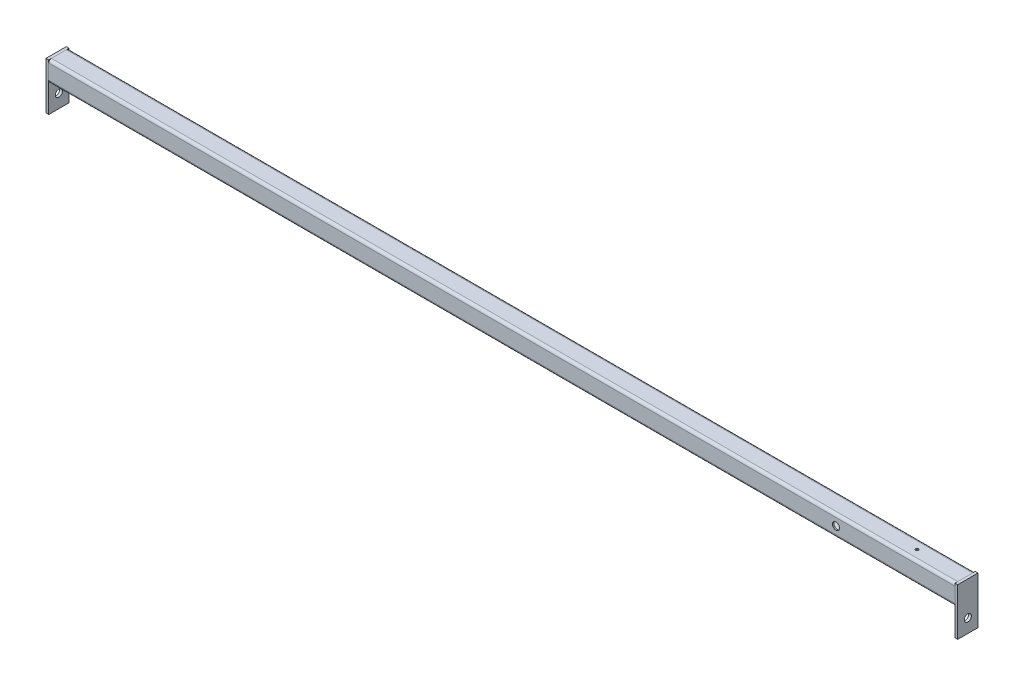
SolidWorks part; units mm, degrees
other "DetailItem1"
other "DetailItem2"
other "Weld Folder"
other "Weld Bead1"
other "Weld Bead2"
material "AISI 304"
ref_plane "Front Plane" through (0, 0, 0) normal (0, 0, 1) x (1, 0, 0)
ref_plane "Top Plane" through (0, 0, 0) normal (0, 1, 0) x (1, 0, 0)
ref_plane "Right Plane" through (0, 0, 0) normal (1, 0, 0) x (0, 0, -1)
sketch3d "3DStructure"
  line L0 (0, 0, 0) -> (0, 70, 0)
  line L2 (1344, 70, 0) -> (1344, 0, 0)
  line L3 (0, 55, 0) -> (1344, 55, 0)
  dimension "D3" = 15
  dimension "D1" = 1344
  dimension "D2" = 15
  dimension "D4" = 70
other "Square tube - configured 30 X 30 X 2"
ref_plane "Plane1" through (0, 55, 0) normal (1, 0, 0) x (0, 0, -1)
sketch "Sketch1" plane through (0, 55, 0) normal (1, 0, 0) x (0, 0, -1)
  line L0 (-11, -13) -> (11, -13)
  line L1 (-13, -11) -> (-13, 11)
  line L2 (11, 13) -> (-11, 13)
  line L3 (13, 11) -> (13, -11)
  line L4 (-11, -15) -> (11, -15)
  line L5 (-15, -11) -> (-15, 11)
  line L6 (11, 15) -> (-11, 15)
  line L7 (15, 11) -> (15, -11)
  arc A0 (15, 11) -> (11, 15) centre (11, 11) ccw
  arc A1 (11, -15) -> (15, -11) centre (11, -11) ccw
  arc A2 (-15, -11) -> (-11, -15) centre (-11, -11) ccw
  arc A3 (-11, 15) -> (-15, 11) centre (-11, 11) ccw
  arc A4 (-11, 13) -> (-13, 11) centre (-11, 11) ccw
  arc A5 (13, 11) -> (11, 13) centre (11, 11) ccw
  arc A6 (11, -13) -> (13, -11) centre (11, -11) ccw
  arc A7 (-13, -11) -> (-11, -13) centre (-11, -11) ccw
  point P0 (-15, 0)
  point P1 (15, 0)
  point P2 (0, 15)
  point P3 (0, -15)
  point P4 (0, 0)
  point P5 (-15, -15)
  point P6 (15, -15)
  point P7 (15, 15)
  point P8 (-15, 15)
  point P33 (0, 0)
  dimension "D1" = 4
  dimension "Thickness" = 2
  dimension "V_leg" = 30
other "Steel bar - configured 30 X 2"
ref_plane "Plane2" through (0, 0, 0) normal (0, 1, 0) x (1, 0, 0)
sketch "Sketch11" plane through (0, 0, 0) normal (0, 1, 0) x (1, 0, 0)
  line L9 (2, -15) -> (-2, -15)
  line L10 (2, -15) -> (2, 15)
  line L11 (2, 15) -> (-2, 15)
  line L12 (-2, -15) -> (-2, 15)
  line L13 (2, -15) -> (-2, 15) construction
  line L14 (2, 15) -> (-2, -15) construction
  point P4 (0, 0)
  point P33 (0, 0)
  point P35 (0, 0)
  dimension "D2" = 4
  dimension "D3" = 30
other "Trim/Extend1"
hole_wizard "Ø10.5 (10.5) Frame Mount Holes" positions "Sketch12" profile "Sketch13" hole size "Ø10.5" standard "ANSI Metric" end condition through all
sketch "Sketch12" plane through (1346, 0, 0) normal (1, 0, 0) x (0, 0, -1)
  line L0 (-15, 0) -> (15, 0) construction
  point P0 (0, 20)
  dimension "D1" = 20
sketch "Sketch13" plane through (1346, 20, 0) normal (0, 1, 0) x (0, 0, -1)
  line L0 (0, 0) -> (0, 1348)
  line L1 (0, 1348) -> (5.25, 1348)
  line L2 (5.25, 1348) -> (5.25, 0)
  line L5 (5.25, 0) -> (0, 0)
  line L11 (0, -6.35) -> (0, 107.95) construction
  dimension "Thru Hole Dia." = 10.5
  dimension "Thru Hole Depth" = 1348
hole_wizard "Ø10.5 (10.5) PC Shelf Mount Hole" positions "Sketch14" profile "Sketch16" hole size "Ø10.5" standard "ANSI Metric" end condition through all
sketch "Sketch14" plane through (0, 0, 15) normal (0, 0, 1) x (1, 0, 0)
  line L0 (1346, 0) -> (1346, 70) construction
  line L2 (1342, 44) -> (1342, 66) construction
  point P0 (1166, 55)
  point P11 (1342, 55)
  dimension "D1" = 180
sketch "Sketch16" plane through (1166, 55, 15) normal (1, 0, 0) x (0, -1, 0)
  line L0 (0, 0) -> (0, 30)
  line L1 (0, 30) -> (5.25, 30)
  line L2 (5.25, 30) -> (5.25, 0)
  line L5 (5.25, 0) -> (0, 0)
  line L11 (0, -6.35) -> (0, 107.95) construction
  dimension "Thru Hole Dia." = 10.5
  dimension "Thru Hole Depth" = 30
hole_wizard "Ø5.2 (5.2) Wall Mount Hole" [suppressed] positions "Sketch17" profile "Sketch18" hole size "Ø5.2" standard "ANSI Metric"
sketch "Sketch17" plane through (0, 0, 15) normal (0, 0, 1) x (1, 0, 0)
  line L1 (2, 66) -> (2, 44) construction
  line L2 (-2, 70) -> (-2, 0) construction
  point P0 (672, 55)
  point P10 (2, 55)
  dimension "D1" = 674
sketch "Sketch18" plane through (672, 55, 15) normal (1, 0, 0) x (0, -1, 0)
  line L0 (0, 0) -> (0, 35)
  line L1 (0, 35) -> (2.6, 35)
  line L2 (2.6, 35) -> (2.6, 0)
  line L5 (2.6, 0) -> (0, 0)
  line L11 (0, -6.35) -> (0, 107.95) construction
  dimension "Thru Hole Dia." = 5.2
  dimension "Thru Hole Depth" = 35
hole_wizard "Ø4.2 (4.2) PC Shelf Table Mount Hole" positions "Sketch19" profile "Sketch20" hole size "Ø4.2" standard "ANSI Metric" end condition through all
sketch "Sketch19" plane through (0, 40, 0) normal (0, -1, 0) x (-1, 0, 0)
  line L0 (-1346, -15) -> (-1346, 15) construction
  point P0 (-1271, 0)
  dimension "D1" = 75
sketch "Sketch20" plane through (1271, 40, 0) normal (1, 0, 0) x (0, 0, -1)
  line L0 (0, 0) -> (0, 30)
  line L1 (0, 30) -> (2.1, 30)
  line L2 (2.1, 30) -> (2.1, 0)
  line L5 (2.1, 0) -> (0, 0)
  line L11 (0, -6.35) -> (0, 107.95) construction
  dimension "Thru Hole Dia." = 4.2
  dimension "Thru Hole Depth" = 30
hole_wizard "M6 Clearance Hole table mount" [suppressed] positions "Sketch21" profile "Sketch22" hole size "M6" standard "ANSI Metric"
sketch "Sketch21" plane through (0, 70, 0) normal (0, 1, 0) x (1, 0, 0)
  line L0 (672, -44.1343) -> (672, 40.0748) construction
  line L2 (1342, -15) -> (2, -15) construction
  point P0 (77, 0)
  point P2 (472, 0)
  point P4 (872, 0)
  point P6 (1267, 0)
  point P17 (672, -15)
  dimension "D1" = 400
  dimension "D2" = 395
  dimension "D3" = 395
sketch "Sketch22" plane through (77, 70, 0) normal (1, 0, 0) x (0, 0, 1)
  line L0 (0, 0) -> (0, 70)
  line L1 (0, 70) -> (3.2, 70)
  line L2 (3.2, 70) -> (3.2, 0)
  line L5 (3.2, 0) -> (0, 0)
  line L11 (0, -6.35) -> (0, 107.95) construction
  dimension "Thru Hole Dia." = 6.4
  dimension "Thru Hole Depth" = 70
equation "\"D3@3DStructure\"=\"D2@3DStructure\""
equation "\"D2@Sketch21\"=\"D3@Sketch21\""
